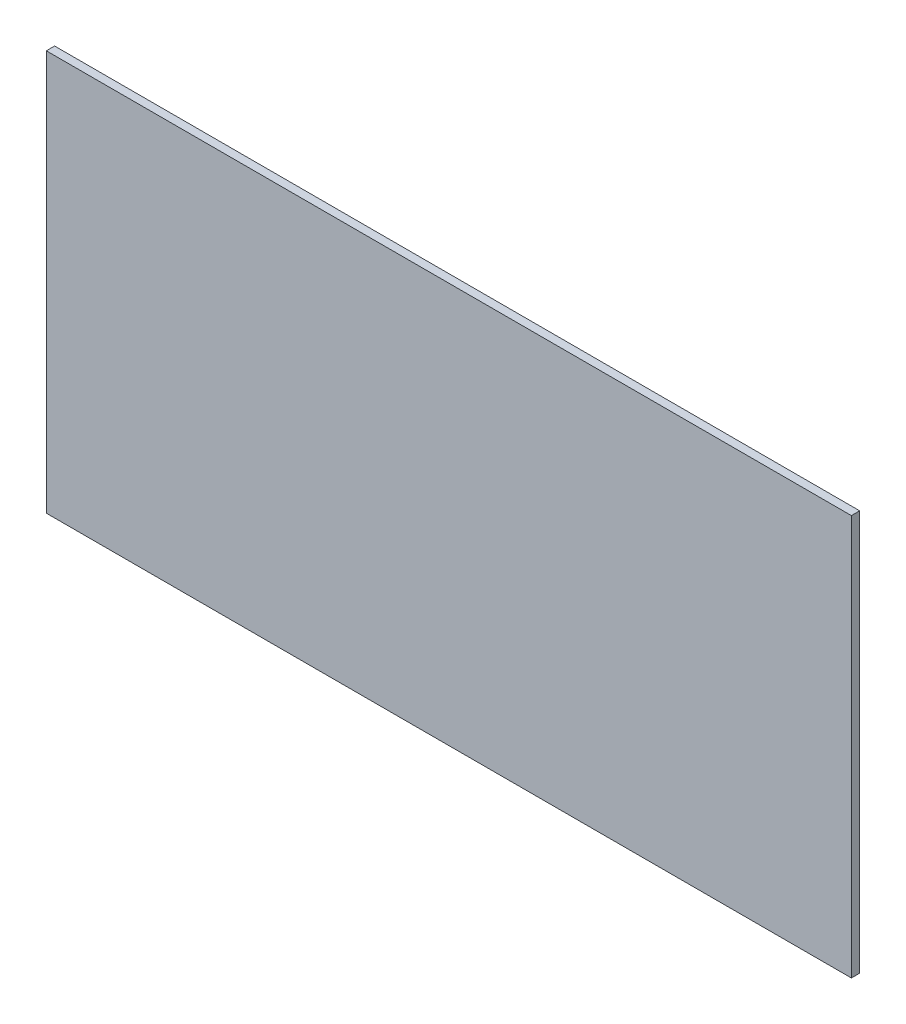
SolidWorks part; units mm, degrees
material "Akryl (středně-vysoký dopad)"
ref_plane "Přední rovina" through (0, 0, 0) normal (0, 0, 1) x (1, 0, 0)
ref_plane "Horní rovina" through (0, 0, 0) normal (0, 1, 0) x (1, 0, 0)
ref_plane "Pravá rovina" through (0, 0, 0) normal (1, 0, 0) x (0, 0, -1)
sketch "Skica1" plane through (0, 0, 0) normal (0, 0, 1) x (1, 0, 0)
  line L1 (194, -96.5) -> (-194, -96.5)
  line L2 (194, -96.5) -> (194, 96.5)
  line L3 (194, 96.5) -> (-194, 96.5)
  line L4 (-194, -96.5) -> (-194, 96.5)
  line L5 (194, -96.5) -> (-194, 96.5) construction
  line L6 (194, 96.5) -> (-194, -96.5) construction
  point P0 (0, 0)
  dimension "D1" = 388
  dimension "D2" = 193
extrude "Přidat vysunutím1" add sketch "Skica1" along normal blind 4
